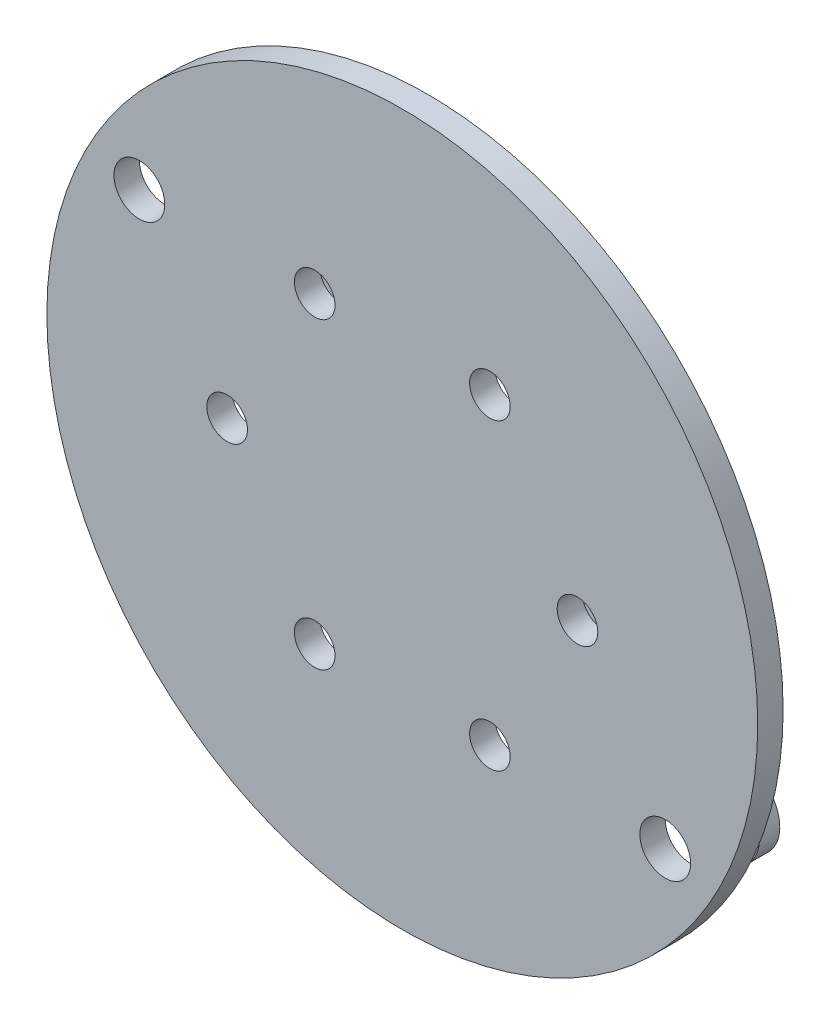
SolidWorks part; units mm, degrees
ref_plane "前视基准面" through (0, 0, 0) normal (0, 0, 1) x (1, 0, 0)
ref_plane "上视基准面" through (0, 0, 0) normal (0, 1, 0) x (1, 0, 0)
ref_plane "右视基准面" through (0, 0, 0) normal (1, 0, 0) x (0, 0, -1)
sketch "草图1" plane through (0, 0, 0) normal (0, 0, 1) x (1, 0, 0)
  circle A0 centre (0, 0) radius 35
  circle A1 centre (0, 0) radius 17.25 construction
  circle A2 centre (17.25, 0) radius 2
  circle A3 centre (8.625, -14.9389) radius 2
  circle A4 centre (-8.625, -14.9389) radius 2
  circle A5 centre (-17.25, 0) radius 2
  circle A6 centre (-8.625, 14.9389) radius 2
  circle A7 centre (8.625, 14.9389) radius 2
  point P18 (0, 0)
  dimension "D1" = 70
  dimension "D2" = 34.5
  dimension "D3" = 4
  dimension "D4" = 6
extrude "凸台-拉伸1" add sketch "草图1" along normal blind 2.5
sketch "草图2" plane through (0, 0, 0) normal (0, 0, -1) x (-1, 0, 0)
  circle A0 centre (0, 0) radius 5
  dimension "D1" = 10
extrude "凸台-拉伸2" add sketch "草图2" along normal blind 5
sketch "草图3" plane through (0, 0, -5) normal (0, 0, -1) x (-1, 0, 0)
  line L0 (0, 0) -> (-25.8901, -15.1559) construction
  line L1 (0, 0) -> (-25.8901, -15.1559) construction
  line L2 (1.9107, -3.264) -> (-23.9794, -18.42)
  line L3 (-1.9107, 3.264) -> (-27.8009, -11.8919)
  arc A0 (1.9107, -3.264) -> (-1.9107, 3.264) centre (0, 0) ccw
  arc A1 (-27.8009, -11.8919) -> (-23.9794, -18.42) centre (-25.8901, -15.1559) ccw
  point P3 (-12.9451, -7.578)
  dimension "D2" = 3.7822
  dimension "D1" = 30
extrude "凸台-拉伸3" add sketch "草图3" against normal blind 2
sketch "草图5" plane through (0, 0, -5) normal (0, 0, -1) x (-1, 0, 0)
  line L0 (-25.8901, -15.1559) -> (0, 0) construction
  line L1 (0, 0) -> (25.8901, 15.1559) construction
  line L2 (-4.7331, 1.6119) -> (-27.8009, -11.8919)
  line L3 (-23.9794, -18.42) -> (-0.9116, -4.9162)
  line L4 (-4.7331, 1.6119) -> (-27.8009, -11.8919)
  line L5 (-23.9794, -18.42) -> (-0.9116, -4.9162)
  line L6 (0, 0) -> (25.8901, 15.1559) construction
  line L7 (-1.8945, 3.2363) -> (23.9956, 18.3922)
  line L8 (1.8945, -3.2363) -> (27.7846, 11.9197)
  arc A0 (-1.8945, 3.2363) -> (1.8945, -3.2363) centre (0, 0) ccw
  arc A1 (27.7846, 11.9197) -> (23.9956, 18.3922) centre (25.8901, 15.1559) ccw
  arc A2 (-0.9116, -4.9162) -> (-4.7331, 1.6119) centre (0, 0) ccw
  arc A3 (-27.8009, -11.8919) -> (-23.9794, -18.42) centre (-25.8901, -15.1559) ccw
  arc A4 (-0.9116, -4.9162) -> (-4.7331, 1.6119) centre (0, 0) ccw
  arc A5 (-27.8009, -11.8919) -> (-23.9794, -18.42) centre (-25.8901, -15.1559) ccw
  point P0 (12.9451, 7.578)
  arc M8 (-0.9116, -4.9162) -> (-4.7331, 1.6119) centre (0, 0) ccw
  dimension "D2" = 30
  dimension "D3" = 7.5
  dimension "D1" = 0
extrude "凸台-拉伸4" add sketch "草图5" against normal blind 2 contours L8 A1 L7 M8
sketch "草图6" plane through (0, 0, -5) normal (0, 0, -1) x (-1, 0, 0)
  line L4 (4.7486, -1.5655) -> (27.7846, 11.9197)
  line L5 (23.9956, 18.3922) -> (0.9596, 4.907)
  line L6 (-4.7331, 1.6119) -> (-27.8009, -11.8919)
  line L7 (-23.9794, -18.42) -> (-0.9116, -4.9162)
  line L8 (4.7486, -1.5655) -> (27.7846, 11.9197)
  line L9 (23.9956, 18.3922) -> (0.9596, 4.907)
  line L10 (-4.7331, 1.6119) -> (-27.8009, -11.8919)
  line L11 (-23.9794, -18.42) -> (-0.9116, -4.9162)
  circle A0 centre (-25.8901, -15.1559) radius 2.5
  circle A1 centre (25.8901, 15.1559) radius 2.5
  arc A4 (-0.9116, -4.9162) -> (4.7486, -1.5655) centre (0, 0) ccw
  arc A5 (27.7846, 11.9197) -> (23.9956, 18.3922) centre (25.8901, 15.1559) ccw
  arc A6 (0.9596, 4.907) -> (-4.7331, 1.6119) centre (0, 0) ccw
  arc A7 (-27.8009, -11.8919) -> (-23.9794, -18.42) centre (-25.8901, -15.1559) ccw
  arc A8 (-0.9116, -4.9162) -> (4.7486, -1.5655) centre (0, 0) ccw
  arc A9 (27.7846, 11.9197) -> (23.9956, 18.3922) centre (25.8901, 15.1559) ccw
  arc A10 (0.9596, 4.907) -> (-4.7331, 1.6119) centre (0, 0) ccw
  arc A11 (-27.8009, -11.8919) -> (-23.9794, -18.42) centre (-25.8901, -15.1559) ccw
  dimension "D2" = 5
  dimension "D3" = 5
  dimension "D1" = 0
extrude "切除-拉伸1" cut sketch "草图6" against normal through all contours A0 | A1
